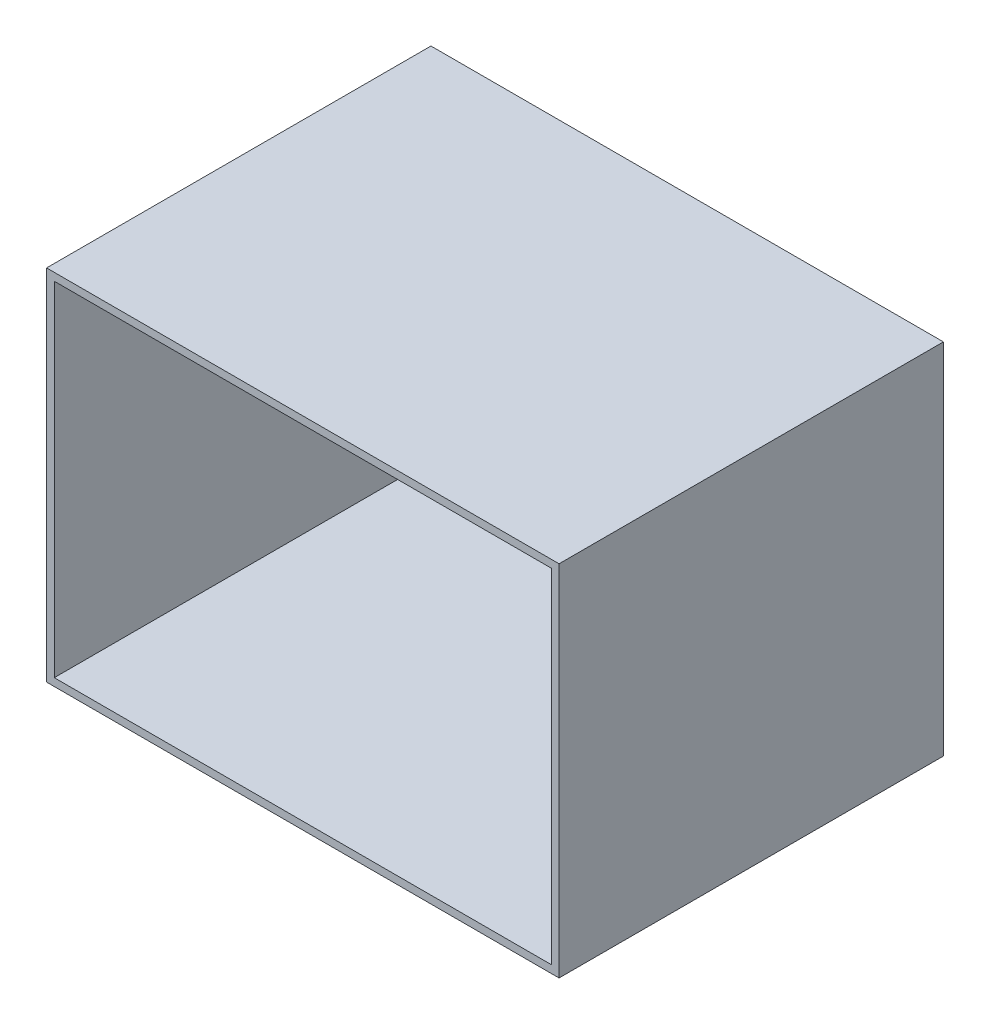
SolidWorks part; units mm, degrees
material "ABS"
ref_plane "Alzado" through (0, 0, 0) normal (0, 0, 1) x (1, 0, 0)
ref_plane "Planta" through (0, 0, 0) normal (0, 1, 0) x (1, 0, 0)
ref_plane "Vista lateral" through (0, 0, 0) normal (1, 0, 0) x (0, 0, -1)
sketch "Croquis1" plane through (0, 0, 0) normal (0, 1, 0) x (1, 0, 0)
  line L1 (0, 0) -> (200, 0)
  line L2 (0, 0) -> (0, 150)
  line L3 (0, 150) -> (200, 150)
  line L4 (200, 0) -> (200, 150)
  dimension "D1" = 150
  dimension "D2" = 200
extrude "Saliente-Extruir1" add sketch "Croquis1" along normal blind 3
sketch "Croquis2" plane through (0, 3, 0) normal (0, 1, 0) x (1, 0, 0)
  line L0 (0, 0) -> (200, 0) construction
  line L1 (0, 150) -> (3, 150)
  line L2 (0, 150) -> (0, 0)
  line L3 (0, 0) -> (3, 0)
  line L4 (3, 150) -> (3, 0)
  line L6 (200, 150) -> (197, 150)
  line L7 (200, 150) -> (200, 0)
  line L8 (200, 0) -> (197, 0)
  line L9 (197, 150) -> (197, 0)
  dimension "D1" = 3
  dimension "D2" = 3
extrude "Saliente-Extruir2" add sketch "Croquis2" along normal blind 134
sketch "Croquis3" plane through (0, 137, 0) normal (0, 1, 0) x (1, 0, 0)
  line L1 (0, 150) -> (200, 150)
  line L2 (0, 150) -> (0, 0)
  line L3 (0, 0) -> (200, 0)
  line L4 (200, 150) -> (200, 0)
extrude "Saliente-Extruir3" add sketch "Croquis3" along normal blind 3
